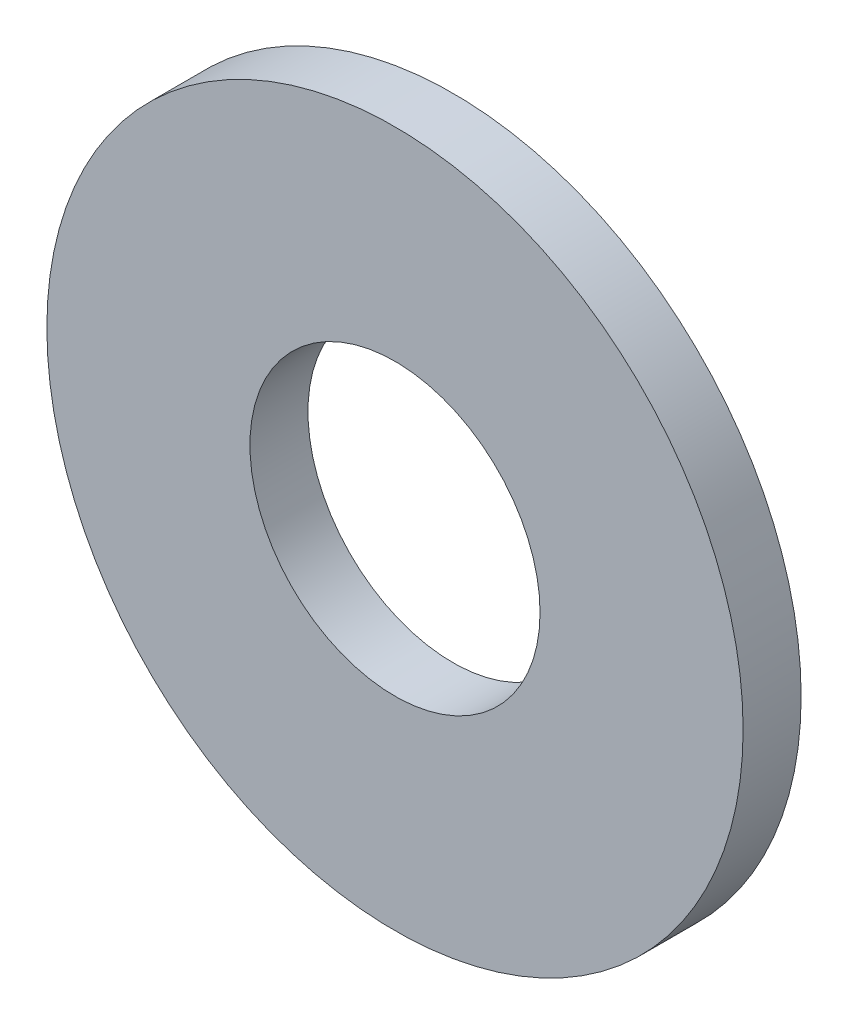
SolidWorks part; units mm, degrees
ref_plane "前视基准面" through (0, 0, 0) normal (0, 0, 1) x (1, 0, 0)
ref_plane "上视基准面" through (0, 0, 0) normal (0, 1, 0) x (1, 0, 0)
ref_plane "右视基准面" through (0, 0, 0) normal (1, 0, 0) x (0, 0, -1)
sketch "草图1" plane through (0, 0, 0) normal (0, 0, 1) x (1, 0, 0)
  circle A0 centre (0, 0) radius 12
  circle A1 centre (0, 0) radius 5
  dimension "D1" = 10
  dimension "D2" = 24
extrude "凸台-拉伸1" add sketch "草图1" along normal blind 2
